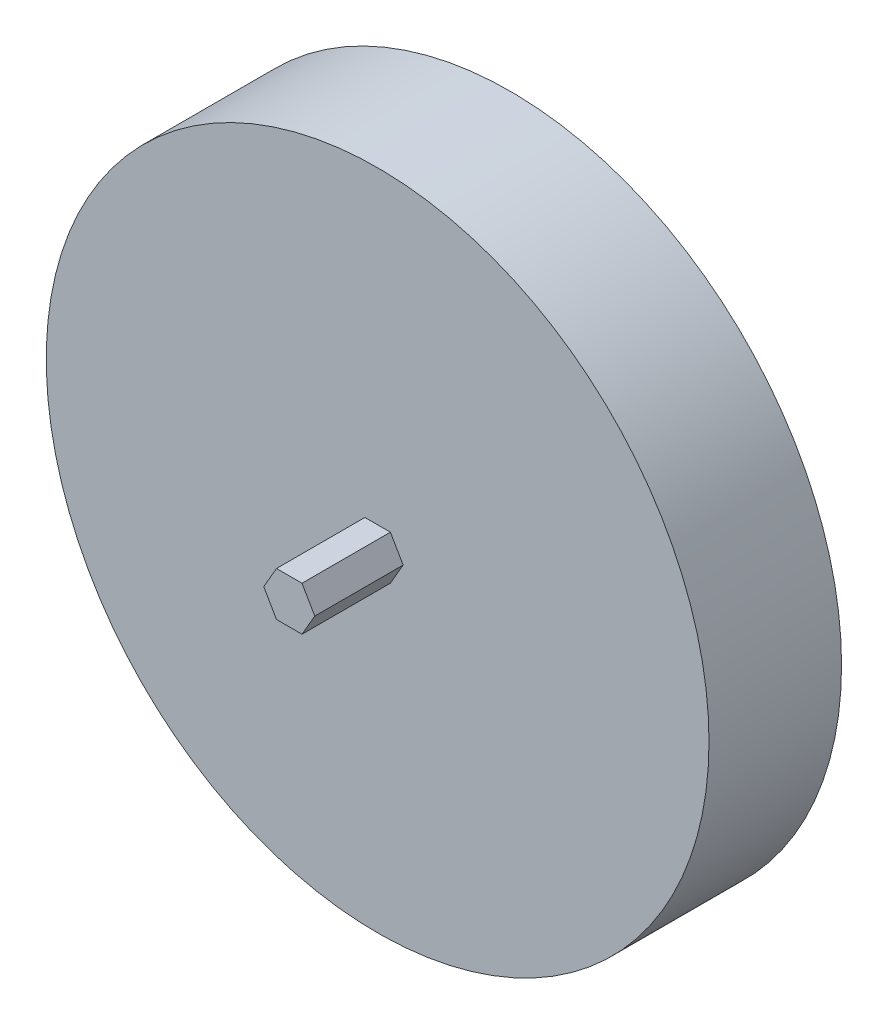
SolidWorks part; units mm, degrees
ref_plane "Front Plane" through (0, 0, 0) normal (0, 0, 1) x (1, 0, 0)
ref_plane "Top Plane" through (0, 0, 0) normal (0, 1, 0) x (1, 0, 0)
ref_plane "Right Plane" through (0, 0, 0) normal (1, 0, 0) x (0, 0, -1)
sketch "Sketch1" plane through (0, 0, 0) normal (0, 0, 1) x (1, 0, 0)
  circle A0 centre (0, 0) radius 15
  dimension "D1" = 30
extrude "Boss-Extrude1" add sketch "Sketch1" along normal blind 6
sketch "Sketch4" plane through (0, 0, 6) normal (0, 0, 1) x (1, 0, 0)
  line L1 (1.1547, 0) -> (0.5774, 1)
  line L2 (0.5774, 1) -> (-0.5774, 1)
  line L3 (-0.5774, 1) -> (-1.1547, 0)
  line L4 (-1.1547, 0) -> (-0.5774, -1)
  line L5 (-0.5774, -1) -> (0.5774, -1)
  line L6 (0.5774, -1) -> (1.1547, 0)
  circle A0 centre (0, 0) radius 1 construction
  point P1 (0, 0)
  dimension "D1" = 2
extrude "Boss-Extrude2" add sketch "Sketch4" along normal blind 4
